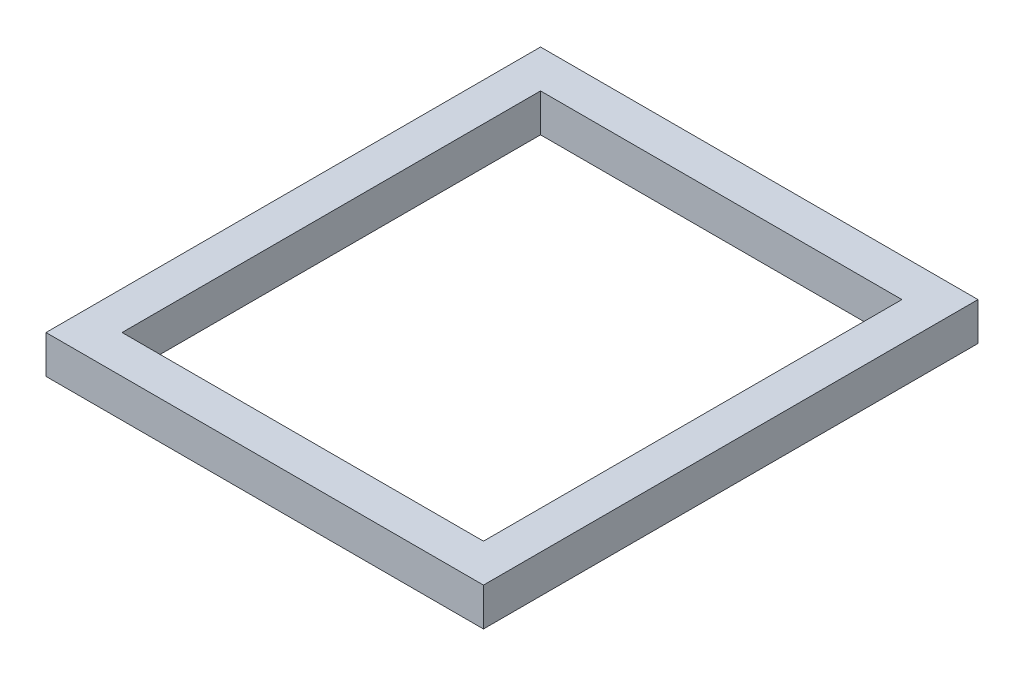
SolidWorks part; units mm, degrees
ref_plane "Front Plane" through (0, 0, 0) normal (0, 0, 1) x (1, 0, 0)
ref_plane "Top Plane" through (0, 0, 0) normal (0, 1, 0) x (1, 0, 0)
ref_plane "Right Plane" through (0, 0, 0) normal (1, 0, 0) x (0, 0, -1)
sketch "Sketch1" plane through (0, 0, 0) normal (0, 1, 0) x (1, 0, 0)
  line L1 (-36.5125, -41.275) -> (36.5125, -41.275)
  line L2 (-36.5125, -41.275) -> (-36.5125, 41.275)
  line L3 (-36.5125, 41.275) -> (36.5125, 41.275)
  line L4 (36.5125, -41.275) -> (36.5125, 41.275)
  line L5 (-36.5125, -41.275) -> (36.5125, 41.275) construction
  line L6 (-36.5125, 41.275) -> (36.5125, -41.275) construction
  line L7 (-30.1625, -34.925) -> (30.1625, -34.925)
  line L8 (-30.1625, -34.925) -> (-30.1625, 34.925)
  line L9 (-30.1625, 34.925) -> (30.1625, 34.925)
  line L10 (30.1625, -34.925) -> (30.1625, 34.925)
  line L11 (-30.1625, -34.925) -> (30.1625, 34.925) construction
  line L12 (-30.1625, 34.925) -> (30.1625, -34.925) construction
  point P0 (0, 0)
  point P5 (0, 0)
  dimension "D3" = 6.35
  dimension "D1" = 73.025
  dimension "D2" = 82.55
  dimension "D4" = 6.35
extrude "Boss-Extrude1" add sketch "Sketch1" along normal blind 6.35
